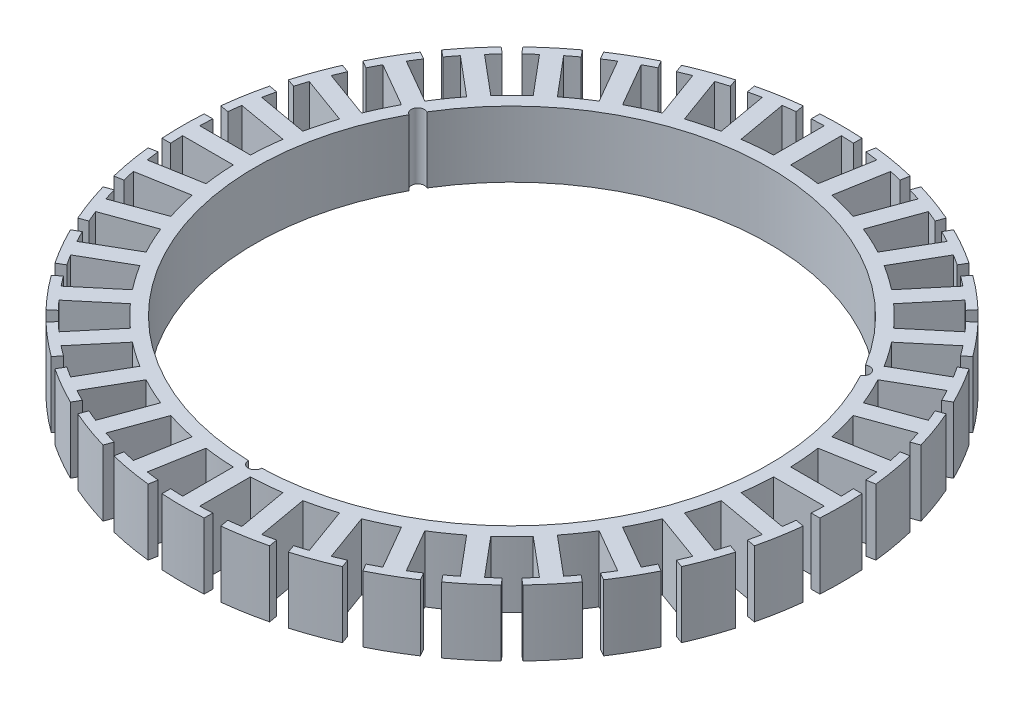
SolidWorks part; units mm, degrees
ref_plane "Alzado" through (0, 0, 0) normal (0, 0, 1) x (1, 0, 0)
ref_plane "Planta" through (0, 0, 0) normal (0, 1, 0) x (1, 0, 0)
ref_plane "Vista lateral" through (0, 0, 0) normal (1, 0, 0) x (0, 0, -1)
sketch "Croquis1" plane through (0, 0, 0) normal (0, 1, 0) x (1, 0, 0)
  line L0 (0, 0) -> (0, -50) construction
  line L1 (0, 0) -> (-6.2386, -71.3072) construction
  line L2 (0, 0) -> (6.3179, -72.2144) construction
  line L3 (-1.3, -40.9794) -> (-1.3, -48.6662)
  line L4 (1.3, -40.9794) -> (1.3, -48.6662)
  line L5 (-3.2, -49.8975) -> (-3.2, -48.5783)
  line L6 (3.2, -49.8975) -> (3.2, -48.5783)
  line L7 (-11.816, -48.5838) -> (-11.5869, -47.2846)
  line L8 (-5.5132, -49.6951) -> (-5.2841, -48.3959)
  line L9 (-5.8357, -40.5826) -> (-7.1705, -48.1526)
  line L10 (-8.3962, -40.1311) -> (-9.731, -47.7011)
  line L11 (-20.073, -45.7938) -> (-19.6218, -44.5542)
  line L12 (-14.0589, -47.9828) -> (-13.6077, -46.7431)
  line L13 (-12.7942, -38.9527) -> (-15.4232, -46.1759)
  line L14 (-15.2374, -38.0634) -> (-17.8664, -45.2866)
  line L15 (-27.72, -41.6125) -> (-27.0604, -40.47)
  line L16 (-22.1775, -44.8125) -> (-21.5179, -43.67)
  line L17 (-19.3639, -36.1392) -> (-23.2073, -42.7962)
  line L18 (-21.6155, -34.8392) -> (-25.4589, -41.4962)
  line L19 (-34.5248, -36.1668) -> (-33.6769, -35.1562)
  line L20 (-29.6221, -40.2806) -> (-28.7742, -39.27)
  line L21 (-25.3452, -32.2277) -> (-30.2862, -38.1161)
  line L22 (-27.3369, -30.5564) -> (-32.2779, -36.4449)
  line L23 (-40.2806, -29.6221) -> (-39.27, -28.7742)
  line L24 (-36.1668, -34.5248) -> (-35.1562, -33.6769)
  line L25 (-30.5564, -27.3369) -> (-36.4449, -32.2779)
  line L26 (-32.2277, -25.3452) -> (-38.1161, -30.2862)
  line L27 (-44.8125, -22.1775) -> (-43.67, -21.5179)
  line L28 (-41.6125, -27.72) -> (-40.47, -27.0604)
  line L29 (-34.8392, -21.6155) -> (-41.4962, -25.4589)
  line L30 (-36.1392, -19.3639) -> (-42.7962, -23.2073)
  line L31 (-47.9828, -14.0589) -> (-46.7431, -13.6077)
  line L32 (-45.7938, -20.073) -> (-44.5542, -19.6218)
  line L33 (-38.0634, -15.2374) -> (-45.2866, -17.8664)
  line L34 (-38.9527, -12.7942) -> (-46.1759, -15.4232)
  line L35 (-49.6951, -5.5132) -> (-48.3959, -5.2841)
  line L36 (-48.5838, -11.816) -> (-47.2846, -11.5869)
  line L37 (-40.1311, -8.3962) -> (-47.7011, -9.731)
  line L38 (-40.5826, -5.8357) -> (-48.1526, -7.1705)
  line L39 (-49.8975, 3.2) -> (-48.5783, 3.2)
  line L40 (-49.8975, -3.2) -> (-48.5783, -3.2)
  line L41 (-40.9794, -1.3) -> (-48.6662, -1.3)
  line L42 (-40.9794, 1.3) -> (-48.6662, 1.3)
  line L43 (-48.5838, 11.816) -> (-47.2846, 11.5869)
  line L44 (-49.6951, 5.5132) -> (-48.3959, 5.2841)
  line L45 (-40.5826, 5.8357) -> (-48.1526, 7.1705)
  line L46 (-40.1311, 8.3962) -> (-47.7011, 9.731)
  line L47 (-45.7938, 20.073) -> (-44.5542, 19.6218)
  line L48 (-47.9828, 14.0589) -> (-46.7431, 13.6077)
  line L49 (-38.9527, 12.7942) -> (-46.1759, 15.4232)
  line L50 (-38.0634, 15.2374) -> (-45.2866, 17.8664)
  line L51 (-41.6125, 27.72) -> (-40.47, 27.0604)
  line L52 (-44.8125, 22.1775) -> (-43.67, 21.5179)
  line L53 (-36.1392, 19.3639) -> (-42.7962, 23.2073)
  line L54 (-34.8392, 21.6155) -> (-41.4962, 25.4589)
  line L55 (-36.1668, 34.5248) -> (-35.1562, 33.6769)
  line L56 (-40.2806, 29.6221) -> (-39.27, 28.7742)
  line L57 (-32.2277, 25.3452) -> (-38.1161, 30.2862)
  line L58 (-30.5564, 27.3369) -> (-36.4449, 32.2779)
  line L59 (-29.6221, 40.2806) -> (-28.7742, 39.27)
  line L60 (-34.5248, 36.1668) -> (-33.6769, 35.1562)
  line L61 (-27.3369, 30.5564) -> (-32.2779, 36.4449)
  line L62 (-25.3452, 32.2277) -> (-30.2862, 38.1161)
  line L63 (-22.1775, 44.8125) -> (-21.5179, 43.67)
  line L64 (-27.72, 41.6125) -> (-27.0604, 40.47)
  line L65 (-21.6155, 34.8392) -> (-25.4589, 41.4962)
  line L66 (-19.3639, 36.1392) -> (-23.2073, 42.7962)
  line L67 (-14.0589, 47.9828) -> (-13.6077, 46.7431)
  line L68 (-20.073, 45.7938) -> (-19.6218, 44.5542)
  line L69 (-15.2374, 38.0634) -> (-17.8664, 45.2866)
  line L70 (-12.7942, 38.9527) -> (-15.4232, 46.1759)
  line L71 (-5.5132, 49.6951) -> (-5.2841, 48.3959)
  line L72 (-11.816, 48.5838) -> (-11.5869, 47.2846)
  line L73 (-8.3962, 40.1311) -> (-9.731, 47.7011)
  line L74 (-5.8357, 40.5826) -> (-7.1705, 48.1526)
  line L75 (3.2, 49.8975) -> (3.2, 48.5783)
  line L76 (-3.2, 49.8975) -> (-3.2, 48.5783)
  line L77 (-1.3, 40.9794) -> (-1.3, 48.6662)
  line L78 (1.3, 40.9794) -> (1.3, 48.6662)
  line L79 (11.816, 48.5838) -> (11.5869, 47.2846)
  line L80 (5.5132, 49.6951) -> (5.2841, 48.3959)
  line L81 (5.8357, 40.5826) -> (7.1705, 48.1526)
  line L82 (8.3962, 40.1311) -> (9.731, 47.7011)
  line L83 (20.073, 45.7938) -> (19.6218, 44.5542)
  line L84 (14.0589, 47.9828) -> (13.6077, 46.7431)
  line L85 (12.7942, 38.9527) -> (15.4232, 46.1759)
  line L86 (15.2374, 38.0634) -> (17.8664, 45.2866)
  line L87 (27.72, 41.6125) -> (27.0604, 40.47)
  line L88 (22.1775, 44.8125) -> (21.5179, 43.67)
  line L89 (19.3639, 36.1392) -> (23.2073, 42.7962)
  line L90 (21.6155, 34.8392) -> (25.4589, 41.4962)
  line L91 (34.5248, 36.1668) -> (33.6769, 35.1562)
  line L92 (29.6221, 40.2806) -> (28.7742, 39.27)
  line L93 (25.3452, 32.2277) -> (30.2862, 38.1161)
  line L94 (27.3369, 30.5564) -> (32.2779, 36.4449)
  line L95 (40.2806, 29.6221) -> (39.27, 28.7742)
  line L96 (36.1668, 34.5248) -> (35.1562, 33.6769)
  line L97 (30.5564, 27.3369) -> (36.4449, 32.2779)
  line L98 (32.2277, 25.3452) -> (38.1161, 30.2862)
  line L99 (44.8125, 22.1775) -> (43.67, 21.5179)
  line L100 (41.6125, 27.72) -> (40.47, 27.0604)
  line L101 (34.8392, 21.6155) -> (41.4962, 25.4589)
  line L102 (36.1392, 19.3639) -> (42.7962, 23.2073)
  line L103 (47.9828, 14.0589) -> (46.7431, 13.6077)
  line L104 (45.7938, 20.073) -> (44.5542, 19.6218)
  line L105 (38.0634, 15.2374) -> (45.2866, 17.8664)
  line L106 (38.9527, 12.7942) -> (46.1759, 15.4232)
  line L107 (49.6951, 5.5132) -> (48.3959, 5.2841)
  line L108 (48.5838, 11.816) -> (47.2846, 11.5869)
  line L109 (40.1311, 8.3962) -> (47.7011, 9.731)
  line L110 (40.5826, 5.8357) -> (48.1526, 7.1705)
  line L111 (49.8975, -3.2) -> (48.5783, -3.2)
  line L112 (49.8975, 3.2) -> (48.5783, 3.2)
  line L113 (40.9794, 1.3) -> (48.6662, 1.3)
  line L114 (40.9794, -1.3) -> (48.6662, -1.3)
  line L115 (48.5838, -11.816) -> (47.2846, -11.5869)
  line L116 (49.6951, -5.5132) -> (48.3959, -5.2841)
  line L117 (40.5826, -5.8357) -> (48.1526, -7.1705)
  line L118 (40.1311, -8.3962) -> (47.7011, -9.731)
  line L119 (45.7938, -20.073) -> (44.5542, -19.6218)
  line L120 (47.9828, -14.0589) -> (46.7431, -13.6077)
  line L121 (38.9527, -12.7942) -> (46.1759, -15.4232)
  line L122 (38.0634, -15.2374) -> (45.2866, -17.8664)
  line L123 (41.6125, -27.72) -> (40.47, -27.0604)
  line L124 (44.8125, -22.1775) -> (43.67, -21.5179)
  line L125 (36.1392, -19.3639) -> (42.7962, -23.2073)
  line L126 (34.8392, -21.6155) -> (41.4962, -25.4589)
  line L127 (36.1668, -34.5248) -> (35.1562, -33.6769)
  line L128 (40.2806, -29.6221) -> (39.27, -28.7742)
  line L129 (32.2277, -25.3452) -> (38.1161, -30.2862)
  line L130 (30.5564, -27.3369) -> (36.4449, -32.2779)
  line L131 (29.6221, -40.2806) -> (28.7742, -39.27)
  line L132 (34.5248, -36.1668) -> (33.6769, -35.1562)
  line L133 (27.3369, -30.5564) -> (32.2779, -36.4449)
  line L134 (25.3452, -32.2277) -> (30.2862, -38.1161)
  line L135 (22.1775, -44.8125) -> (21.5179, -43.67)
  line L136 (27.72, -41.6125) -> (27.0604, -40.47)
  line L137 (21.6155, -34.8392) -> (25.4589, -41.4962)
  line L138 (19.3639, -36.1392) -> (23.2073, -42.7962)
  line L139 (14.0589, -47.9828) -> (13.6077, -46.7431)
  line L140 (20.073, -45.7938) -> (19.6218, -44.5542)
  line L141 (15.2374, -38.0634) -> (17.8664, -45.2866)
  line L142 (12.7942, -38.9527) -> (15.4232, -46.1759)
  line L143 (5.5132, -49.6951) -> (5.2841, -48.3959)
  line L144 (11.816, -48.5838) -> (11.5869, -47.2846)
  line L145 (8.3962, -40.1311) -> (9.731, -47.7011)
  line L146 (5.8357, -40.5826) -> (7.1705, -48.1526)
  arc A0 (-3.2, -49.8975) -> (3.2, -49.8975) centre (0, 0) ccw
  arc A1 (-3.3991, -38.8516) -> (3.3991, -38.8516) centre (0, 0) ccw
  arc A2 (1.3, -40.9794) -> (3.5734, -40.844) centre (0, 0) ccw
  arc A3 (-3.2, -48.5783) -> (-1.3, -48.6662) centre (0, 0) ccw
  arc A4 (1.3, -48.6662) -> (3.2, -48.5783) centre (0, 0) ccw
  arc A5 (-3.5734, -40.844) -> (-1.3, -40.9794) centre (0, 0) ccw
  arc A6 (-11.816, -48.5838) -> (-5.5132, -49.6951) centre (0, 0) ccw
  arc A7 (-11.5869, -47.2846) -> (-9.731, -47.7011) centre (0, 0) ccw
  arc A8 (-7.1705, -48.1526) -> (-5.2841, -48.3959) centre (0, 0) ccw
  arc A9 (-10.6116, -39.603) -> (-8.3962, -40.1311) centre (0, 0) ccw
  arc A10 (-10.0939, -37.6711) -> (-3.3991, -38.8516) centre (0, 0) ccw
  arc A11 (-5.8357, -40.5826) -> (-3.5734, -40.844) centre (0, 0) ccw
  arc A12 (-20.073, -45.7938) -> (-14.0589, -47.9828) centre (0, 0) ccw
  arc A13 (-19.6218, -44.5542) -> (-17.8664, -45.2866) centre (0, 0) ccw
  arc A14 (-15.4232, -46.1759) -> (-13.6077, -46.7431) centre (0, 0) ccw
  arc A15 (-17.3273, -37.1586) -> (-15.2374, -38.0634) centre (0, 0) ccw
  arc A16 (-16.4821, -35.346) -> (-10.0939, -37.6711) centre (0, 0) ccw
  arc A17 (-12.7942, -38.9527) -> (-10.6116, -39.603) centre (0, 0) ccw
  arc A18 (-27.72, -41.6125) -> (-22.1775, -44.8125) centre (0, 0) ccw
  arc A19 (-27.0604, -40.47) -> (-25.4589, -41.4962) centre (0, 0) ccw
  arc A20 (-23.2073, -42.7962) -> (-21.5179, -43.67) centre (0, 0) ccw
  arc A21 (-23.5166, -33.5852) -> (-21.6155, -34.8392) centre (0, 0) ccw
  arc A22 (-22.3695, -31.9469) -> (-16.4821, -35.346) centre (0, 0) ccw
  arc A23 (-19.3639, -36.1392) -> (-17.3273, -37.1586) centre (0, 0) ccw
  arc A24 (-34.5248, -36.1668) -> (-29.6221, -40.2806) centre (0, 0) ccw
  arc A25 (-33.6769, -35.1562) -> (-32.2779, -36.4449) centre (0, 0) ccw
  arc A26 (-30.2862, -38.1161) -> (-28.7742, -39.27) centre (0, 0) ccw
  arc A27 (-28.9914, -28.9914) -> (-27.3369, -30.5564) centre (0, 0) ccw
  arc A28 (-27.5772, -27.5772) -> (-22.3695, -31.9469) centre (0, 0) ccw
  arc A29 (-25.3452, -32.2277) -> (-23.5166, -33.5852) centre (0, 0) ccw
  arc A30 (-40.2806, -29.6221) -> (-36.1668, -34.5248) centre (0, 0) ccw
  arc A31 (-39.27, -28.7742) -> (-38.1161, -30.2862) centre (0, 0) ccw
  arc A32 (-36.4449, -32.2779) -> (-35.1562, -33.6769) centre (0, 0) ccw
  arc A33 (-33.5852, -23.5166) -> (-32.2277, -25.3452) centre (0, 0) ccw
  arc A34 (-31.9469, -22.3695) -> (-27.5772, -27.5772) centre (0, 0) ccw
  arc A35 (-30.5564, -27.3369) -> (-28.9914, -28.9914) centre (0, 0) ccw
  arc A36 (-44.8125, -22.1775) -> (-41.6125, -27.72) centre (0, 0) ccw
  arc A37 (-43.67, -21.5179) -> (-42.7962, -23.2073) centre (0, 0) ccw
  arc A38 (-41.4962, -25.4589) -> (-40.47, -27.0604) centre (0, 0) ccw
  arc A39 (-37.1586, -17.3273) -> (-36.1392, -19.3639) centre (0, 0) ccw
  arc A40 (-35.346, -16.4821) -> (-31.9469, -22.3695) centre (0, 0) ccw
  arc A41 (-34.8392, -21.6155) -> (-33.5852, -23.5166) centre (0, 0) ccw
  arc A42 (-47.9828, -14.0589) -> (-45.7938, -20.073) centre (0, 0) ccw
  arc A43 (-46.7431, -13.6077) -> (-46.1759, -15.4232) centre (0, 0) ccw
  arc A44 (-45.2866, -17.8664) -> (-44.5542, -19.6218) centre (0, 0) ccw
  arc A45 (-39.603, -10.6116) -> (-38.9527, -12.7942) centre (0, 0) ccw
  arc A46 (-37.6711, -10.0939) -> (-35.346, -16.4821) centre (0, 0) ccw
  arc A47 (-38.0634, -15.2374) -> (-37.1586, -17.3273) centre (0, 0) ccw
  arc A48 (-49.6951, -5.5132) -> (-48.5838, -11.816) centre (0, 0) ccw
  arc A49 (-48.3959, -5.2841) -> (-48.1526, -7.1705) centre (0, 0) ccw
  arc A50 (-47.7011, -9.731) -> (-47.2846, -11.5869) centre (0, 0) ccw
  arc A51 (-40.844, -3.5734) -> (-40.5826, -5.8357) centre (0, 0) ccw
  arc A52 (-38.8516, -3.3991) -> (-37.6711, -10.0939) centre (0, 0) ccw
  arc A53 (-40.1311, -8.3962) -> (-39.603, -10.6116) centre (0, 0) ccw
  arc A54 (-49.8975, 3.2) -> (-49.8975, -3.2) centre (0, 0) ccw
  arc A55 (-48.5783, 3.2) -> (-48.6662, 1.3) centre (0, 0) ccw
  arc A56 (-48.6662, -1.3) -> (-48.5783, -3.2) centre (0, 0) ccw
  arc A57 (-40.844, 3.5734) -> (-40.9794, 1.3) centre (0, 0) ccw
  arc A58 (-38.8516, 3.3991) -> (-38.8516, -3.3991) centre (0, 0) ccw
  arc A59 (-40.9794, -1.3) -> (-40.844, -3.5734) centre (0, 0) ccw
  arc A60 (-48.5838, 11.816) -> (-49.6951, 5.5132) centre (0, 0) ccw
  arc A61 (-47.2846, 11.5869) -> (-47.7011, 9.731) centre (0, 0) ccw
  arc A62 (-48.1526, 7.1705) -> (-48.3959, 5.2841) centre (0, 0) ccw
  arc A63 (-39.603, 10.6116) -> (-40.1311, 8.3962) centre (0, 0) ccw
  arc A64 (-37.6711, 10.0939) -> (-38.8516, 3.3991) centre (0, 0) ccw
  arc A65 (-40.5826, 5.8357) -> (-40.844, 3.5734) centre (0, 0) ccw
  arc A66 (-45.7938, 20.073) -> (-47.9828, 14.0589) centre (0, 0) ccw
  arc A67 (-44.5542, 19.6218) -> (-45.2866, 17.8664) centre (0, 0) ccw
  arc A68 (-46.1759, 15.4232) -> (-46.7431, 13.6077) centre (0, 0) ccw
  arc A69 (-37.1586, 17.3273) -> (-38.0634, 15.2374) centre (0, 0) ccw
  arc A70 (-35.346, 16.4821) -> (-37.6711, 10.0939) centre (0, 0) ccw
  arc A71 (-38.9527, 12.7942) -> (-39.603, 10.6116) centre (0, 0) ccw
  arc A72 (-41.6125, 27.72) -> (-44.8125, 22.1775) centre (0, 0) ccw
  arc A73 (-40.47, 27.0604) -> (-41.4962, 25.4589) centre (0, 0) ccw
  arc A74 (-42.7962, 23.2073) -> (-43.67, 21.5179) centre (0, 0) ccw
  arc A75 (-33.5852, 23.5166) -> (-34.8392, 21.6155) centre (0, 0) ccw
  arc A76 (-31.9469, 22.3695) -> (-35.346, 16.4821) centre (0, 0) ccw
  arc A77 (-36.1392, 19.3639) -> (-37.1586, 17.3273) centre (0, 0) ccw
  arc A78 (-36.1668, 34.5248) -> (-40.2806, 29.6221) centre (0, 0) ccw
  arc A79 (-35.1562, 33.6769) -> (-36.4449, 32.2779) centre (0, 0) ccw
  arc A80 (-38.1161, 30.2862) -> (-39.27, 28.7742) centre (0, 0) ccw
  arc A81 (-28.9914, 28.9914) -> (-30.5564, 27.3369) centre (0, 0) ccw
  arc A82 (-27.5772, 27.5772) -> (-31.9469, 22.3695) centre (0, 0) ccw
  arc A83 (-32.2277, 25.3452) -> (-33.5852, 23.5166) centre (0, 0) ccw
  arc A84 (-29.6221, 40.2806) -> (-34.5248, 36.1668) centre (0, 0) ccw
  arc A85 (-28.7742, 39.27) -> (-30.2862, 38.1161) centre (0, 0) ccw
  arc A86 (-32.2779, 36.4449) -> (-33.6769, 35.1562) centre (0, 0) ccw
  arc A87 (-23.5166, 33.5852) -> (-25.3452, 32.2277) centre (0, 0) ccw
  arc A88 (-22.3695, 31.9469) -> (-27.5772, 27.5772) centre (0, 0) ccw
  arc A89 (-27.3369, 30.5564) -> (-28.9914, 28.9914) centre (0, 0) ccw
  arc A90 (-22.1775, 44.8125) -> (-27.72, 41.6125) centre (0, 0) ccw
  arc A91 (-21.5179, 43.67) -> (-23.2073, 42.7962) centre (0, 0) ccw
  arc A92 (-25.4589, 41.4962) -> (-27.0604, 40.47) centre (0, 0) ccw
  arc A93 (-17.3273, 37.1586) -> (-19.3639, 36.1392) centre (0, 0) ccw
  arc A94 (-16.4821, 35.346) -> (-22.3695, 31.9469) centre (0, 0) ccw
  arc A95 (-21.6155, 34.8392) -> (-23.5166, 33.5852) centre (0, 0) ccw
  arc A96 (-14.0589, 47.9828) -> (-20.073, 45.7938) centre (0, 0) ccw
  arc A97 (-13.6077, 46.7431) -> (-15.4232, 46.1759) centre (0, 0) ccw
  arc A98 (-17.8664, 45.2866) -> (-19.6218, 44.5542) centre (0, 0) ccw
  arc A99 (-10.6116, 39.603) -> (-12.7942, 38.9527) centre (0, 0) ccw
  arc A100 (-10.0939, 37.6711) -> (-16.4821, 35.346) centre (0, 0) ccw
  arc A101 (-15.2374, 38.0634) -> (-17.3273, 37.1586) centre (0, 0) ccw
  arc A102 (-5.5132, 49.6951) -> (-11.816, 48.5838) centre (0, 0) ccw
  arc A103 (-5.2841, 48.3959) -> (-7.1705, 48.1526) centre (0, 0) ccw
  arc A104 (-9.731, 47.7011) -> (-11.5869, 47.2846) centre (0, 0) ccw
  arc A105 (-3.5734, 40.844) -> (-5.8357, 40.5826) centre (0, 0) ccw
  arc A106 (-3.3991, 38.8516) -> (-10.0939, 37.6711) centre (0, 0) ccw
  arc A107 (-8.3962, 40.1311) -> (-10.6116, 39.603) centre (0, 0) ccw
  arc A108 (3.2, 49.8975) -> (-3.2, 49.8975) centre (0, 0) ccw
  arc A109 (3.2, 48.5783) -> (1.3, 48.6662) centre (0, 0) ccw
  arc A110 (-1.3, 48.6662) -> (-3.2, 48.5783) centre (0, 0) ccw
  arc A111 (3.5734, 40.844) -> (1.3, 40.9794) centre (0, 0) ccw
  arc A112 (3.3991, 38.8516) -> (-3.3991, 38.8516) centre (0, 0) ccw
  arc A113 (-1.3, 40.9794) -> (-3.5734, 40.844) centre (0, 0) ccw
  arc A114 (11.816, 48.5838) -> (5.5132, 49.6951) centre (0, 0) ccw
  arc A115 (11.5869, 47.2846) -> (9.731, 47.7011) centre (0, 0) ccw
  arc A116 (7.1705, 48.1526) -> (5.2841, 48.3959) centre (0, 0) ccw
  arc A117 (10.6116, 39.603) -> (8.3962, 40.1311) centre (0, 0) ccw
  arc A118 (10.0939, 37.6711) -> (3.3991, 38.8516) centre (0, 0) ccw
  arc A119 (5.8357, 40.5826) -> (3.5734, 40.844) centre (0, 0) ccw
  arc A120 (20.073, 45.7938) -> (14.0589, 47.9828) centre (0, 0) ccw
  arc A121 (19.6218, 44.5542) -> (17.8664, 45.2866) centre (0, 0) ccw
  arc A122 (15.4232, 46.1759) -> (13.6077, 46.7431) centre (0, 0) ccw
  arc A123 (17.3273, 37.1586) -> (15.2374, 38.0634) centre (0, 0) ccw
  arc A124 (16.4821, 35.346) -> (10.0939, 37.6711) centre (0, 0) ccw
  arc A125 (12.7942, 38.9527) -> (10.6116, 39.603) centre (0, 0) ccw
  arc A126 (27.72, 41.6125) -> (22.1775, 44.8125) centre (0, 0) ccw
  arc A127 (27.0604, 40.47) -> (25.4589, 41.4962) centre (0, 0) ccw
  arc A128 (23.2073, 42.7962) -> (21.5179, 43.67) centre (0, 0) ccw
  arc A129 (23.5166, 33.5852) -> (21.6155, 34.8392) centre (0, 0) ccw
  arc A130 (22.3695, 31.9469) -> (16.4821, 35.346) centre (0, 0) ccw
  arc A131 (19.3639, 36.1392) -> (17.3273, 37.1586) centre (0, 0) ccw
  arc A132 (34.5248, 36.1668) -> (29.6221, 40.2806) centre (0, 0) ccw
  arc A133 (33.6769, 35.1562) -> (32.2779, 36.4449) centre (0, 0) ccw
  arc A134 (30.2862, 38.1161) -> (28.7742, 39.27) centre (0, 0) ccw
  arc A135 (28.9914, 28.9914) -> (27.3369, 30.5564) centre (0, 0) ccw
  arc A136 (27.5772, 27.5772) -> (22.3695, 31.9469) centre (0, 0) ccw
  arc A137 (25.3452, 32.2277) -> (23.5166, 33.5852) centre (0, 0) ccw
  arc A138 (40.2806, 29.6221) -> (36.1668, 34.5248) centre (0, 0) ccw
  arc A139 (39.27, 28.7742) -> (38.1161, 30.2862) centre (0, 0) ccw
  arc A140 (36.4449, 32.2779) -> (35.1562, 33.6769) centre (0, 0) ccw
  arc A141 (33.5852, 23.5166) -> (32.2277, 25.3452) centre (0, 0) ccw
  arc A142 (31.9469, 22.3695) -> (27.5772, 27.5772) centre (0, 0) ccw
  arc A143 (30.5564, 27.3369) -> (28.9914, 28.9914) centre (0, 0) ccw
  arc A144 (44.8125, 22.1775) -> (41.6125, 27.72) centre (0, 0) ccw
  arc A145 (43.67, 21.5179) -> (42.7962, 23.2073) centre (0, 0) ccw
  arc A146 (41.4962, 25.4589) -> (40.47, 27.0604) centre (0, 0) ccw
  arc A147 (37.1586, 17.3273) -> (36.1392, 19.3639) centre (0, 0) ccw
  arc A148 (35.346, 16.4821) -> (31.9469, 22.3695) centre (0, 0) ccw
  arc A149 (34.8392, 21.6155) -> (33.5852, 23.5166) centre (0, 0) ccw
  arc A150 (47.9828, 14.0589) -> (45.7938, 20.073) centre (0, 0) ccw
  arc A151 (46.7431, 13.6077) -> (46.1759, 15.4232) centre (0, 0) ccw
  arc A152 (45.2866, 17.8664) -> (44.5542, 19.6218) centre (0, 0) ccw
  arc A153 (39.603, 10.6116) -> (38.9527, 12.7942) centre (0, 0) ccw
  arc A154 (37.6711, 10.0939) -> (35.346, 16.4821) centre (0, 0) ccw
  arc A155 (38.0634, 15.2374) -> (37.1586, 17.3273) centre (0, 0) ccw
  arc A156 (49.6951, 5.5132) -> (48.5838, 11.816) centre (0, 0) ccw
  arc A157 (48.3959, 5.2841) -> (48.1526, 7.1705) centre (0, 0) ccw
  arc A158 (47.7011, 9.731) -> (47.2846, 11.5869) centre (0, 0) ccw
  arc A159 (40.844, 3.5734) -> (40.5826, 5.8357) centre (0, 0) ccw
  arc A160 (38.8516, 3.3991) -> (37.6711, 10.0939) centre (0, 0) ccw
  arc A161 (40.1311, 8.3962) -> (39.603, 10.6116) centre (0, 0) ccw
  arc A162 (49.8975, -3.2) -> (49.8975, 3.2) centre (0, 0) ccw
  arc A163 (48.5783, -3.2) -> (48.6662, -1.3) centre (0, 0) ccw
  arc A164 (48.6662, 1.3) -> (48.5783, 3.2) centre (0, 0) ccw
  arc A165 (40.844, -3.5734) -> (40.9794, -1.3) centre (0, 0) ccw
  arc A166 (38.8516, -3.3991) -> (38.8516, 3.3991) centre (0, 0) ccw
  arc A167 (40.9794, 1.3) -> (40.844, 3.5734) centre (0, 0) ccw
  arc A168 (48.5838, -11.816) -> (49.6951, -5.5132) centre (0, 0) ccw
  arc A169 (47.2846, -11.5869) -> (47.7011, -9.731) centre (0, 0) ccw
  arc A170 (48.1526, -7.1705) -> (48.3959, -5.2841) centre (0, 0) ccw
  arc A171 (39.603, -10.6116) -> (40.1311, -8.3962) centre (0, 0) ccw
  arc A172 (37.6711, -10.0939) -> (38.8516, -3.3991) centre (0, 0) ccw
  arc A173 (40.5826, -5.8357) -> (40.844, -3.5734) centre (0, 0) ccw
  arc A174 (45.7938, -20.073) -> (47.9828, -14.0589) centre (0, 0) ccw
  arc A175 (44.5542, -19.6218) -> (45.2866, -17.8664) centre (0, 0) ccw
  arc A176 (46.1759, -15.4232) -> (46.7431, -13.6077) centre (0, 0) ccw
  arc A177 (37.1586, -17.3273) -> (38.0634, -15.2374) centre (0, 0) ccw
  arc A178 (35.346, -16.4821) -> (37.6711, -10.0939) centre (0, 0) ccw
  arc A179 (38.9527, -12.7942) -> (39.603, -10.6116) centre (0, 0) ccw
  arc A180 (41.6125, -27.72) -> (44.8125, -22.1775) centre (0, 0) ccw
  arc A181 (40.47, -27.0604) -> (41.4962, -25.4589) centre (0, 0) ccw
  arc A182 (42.7962, -23.2073) -> (43.67, -21.5179) centre (0, 0) ccw
  arc A183 (33.5852, -23.5166) -> (34.8392, -21.6155) centre (0, 0) ccw
  arc A184 (31.9469, -22.3695) -> (35.346, -16.4821) centre (0, 0) ccw
  arc A185 (36.1392, -19.3639) -> (37.1586, -17.3273) centre (0, 0) ccw
  arc A186 (36.1668, -34.5248) -> (40.2806, -29.6221) centre (0, 0) ccw
  arc A187 (35.1562, -33.6769) -> (36.4449, -32.2779) centre (0, 0) ccw
  arc A188 (38.1161, -30.2862) -> (39.27, -28.7742) centre (0, 0) ccw
  arc A189 (28.9914, -28.9914) -> (30.5564, -27.3369) centre (0, 0) ccw
  arc A190 (27.5772, -27.5772) -> (31.9469, -22.3695) centre (0, 0) ccw
  arc A191 (32.2277, -25.3452) -> (33.5852, -23.5166) centre (0, 0) ccw
  arc A192 (29.6221, -40.2806) -> (34.5248, -36.1668) centre (0, 0) ccw
  arc A193 (28.7742, -39.27) -> (30.2862, -38.1161) centre (0, 0) ccw
  arc A194 (32.2779, -36.4449) -> (33.6769, -35.1562) centre (0, 0) ccw
  arc A195 (23.5166, -33.5852) -> (25.3452, -32.2277) centre (0, 0) ccw
  arc A196 (22.3695, -31.9469) -> (27.5772, -27.5772) centre (0, 0) ccw
  arc A197 (27.3369, -30.5564) -> (28.9914, -28.9914) centre (0, 0) ccw
  arc A198 (22.1775, -44.8125) -> (27.72, -41.6125) centre (0, 0) ccw
  arc A199 (21.5179, -43.67) -> (23.2073, -42.7962) centre (0, 0) ccw
  arc A200 (25.4589, -41.4962) -> (27.0604, -40.47) centre (0, 0) ccw
  arc A201 (17.3273, -37.1586) -> (19.3639, -36.1392) centre (0, 0) ccw
  arc A202 (16.4821, -35.346) -> (22.3695, -31.9469) centre (0, 0) ccw
  arc A203 (21.6155, -34.8392) -> (23.5166, -33.5852) centre (0, 0) ccw
  arc A204 (14.0589, -47.9828) -> (20.073, -45.7938) centre (0, 0) ccw
  arc A205 (13.6077, -46.7431) -> (15.4232, -46.1759) centre (0, 0) ccw
  arc A206 (17.8664, -45.2866) -> (19.6218, -44.5542) centre (0, 0) ccw
  arc A207 (10.6116, -39.603) -> (12.7942, -38.9527) centre (0, 0) ccw
  arc A208 (10.0939, -37.6711) -> (16.4821, -35.346) centre (0, 0) ccw
  arc A209 (15.2374, -38.0634) -> (17.3273, -37.1586) centre (0, 0) ccw
  arc A210 (5.5132, -49.6951) -> (11.816, -48.5838) centre (0, 0) ccw
  arc A211 (5.2841, -48.3959) -> (7.1705, -48.1526) centre (0, 0) ccw
  arc A212 (9.731, -47.7011) -> (11.5869, -47.2846) centre (0, 0) ccw
  arc A213 (3.5734, -40.844) -> (5.8357, -40.5826) centre (0, 0) ccw
  arc A214 (3.3991, -38.8516) -> (10.0939, -37.6711) centre (0, 0) ccw
  arc A215 (8.3962, -40.1311) -> (10.6116, -39.603) centre (0, 0) ccw
  point P12 (-1.3, -44.8228)
  point P18 (-3.2, -49.2379)
  dimension "D1" = 100
  dimension "D2" = 78
  dimension "D5" = 82
  dimension "D8" = 97.3671
  dimension "D4" = 5
  dimension "D6" = 1.3
  dimension "D7" = 1.3
  dimension "D9" = 3.2
  dimension "D10" = 3.2
  dimension "D11" = 36
extrude "Saliente-Extruir3" add sketch "Croquis1" along normal blind 10 contours L145 A215 A207 L142 A205 L139 A204 L140 A206 L141 A209 A201 L138 A199 L135 A198 L136 A200 L137 A203 A195 L134 A193 L131 A192 L132 A194 L133 A197 A189 L130 A187 L127 A186 L128 A188 L129 A191 A183 L126 A181 L123 A180 L124 A182 L125 A185 A177 L122 A175 L119
sketch "Croquis2" plane through (0, 0, 0) normal (0, -1, 0) x (-1, 0, 0)
  circle A0 centre (0, -39) radius 1
  circle A1 centre (0, 0) radius 39 construction
  circle A2 centre (-33.775, 19.5) radius 1
  circle A3 centre (33.775, 19.5) radius 1
  dimension "D1" = 2
  dimension "D2" = 3
extrude "Cortar-Extruir1" cut sketch "Croquis2" against normal blind 10
